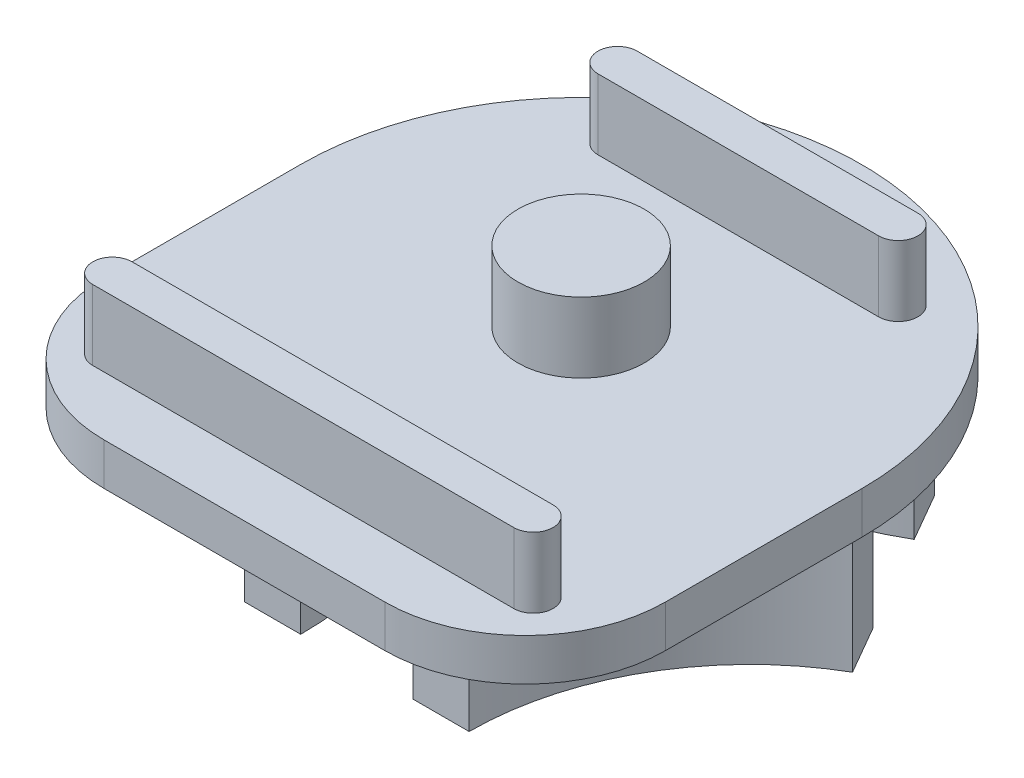
SolidWorks part; units mm, degrees
ref_plane "Front Plane" through (0, 0, 0) normal (0, 0, 1) x (1, 0, 0)
ref_plane "Top Plane" through (0, 0, 0) normal (0, 1, 0) x (1, 0, 0)
ref_plane "Right Plane" through (0, 0, 0) normal (1, 0, 0) x (0, 0, -1)
sketch "Sketch1" plane through (0, 0, 0) normal (0, 1, 0) x (1, 0, 0)
  circle A0 centre (0, 0) radius 28
  circle A1 centre (-28, -48.4974) radius 28
  circle A2 centre (28, -48.4974) radius 28
  arc A3 (-4.6726, -29.6339) -> (4.6726, -29.6339) centre (0, 0) ccw
  arc A4 (0, -37.7271) -> (-4.6726, -29.6339) centre (-28, -48.4974) ccw
  arc A5 (4.6726, -29.6339) -> (0, -37.7271) centre (28, -48.4974) ccw
  circle A6 centre (0, 0) radius 30 construction
  circle A7 centre (-28, -48.4974) radius 30 construction
  circle A8 centre (28, -48.4974) radius 30 construction
  circle A9 centre (0, 0) radius 24
  circle A10 centre (-28, -48.4974) radius 24
  circle A11 centre (28, -48.4974) radius 24
  circle A12 centre (0, 0) radius 20
  circle A13 centre (-28, -48.4974) radius 20
  circle A14 centre (28, -48.4974) radius 20
  dimension "D1" = 56
  dimension "D2" = 2
  dimension "D3" = 4
  dimension "D4" = 4
extrude "Boss-Extrude1" add sketch "Sketch1" along normal blind 10 contours A10 A13 | A9 A12 | A11 A14 | A5 A3 A4
sketch "Sketch2" plane through (0, 10, 0) normal (0, 1, 0) x (1, 0, 0)
  line L0 (-20, -32.517) -> (-20, -56.5059)
  line L1 (-20, -56.5059) -> (20, -56.5059)
  line L2 (20, -56.5059) -> (20, -32.517)
  arc A0 (20, -32.517) -> (-20, -32.517) centre (0, -32.517) ccw
  dimension "D1" = 40
extrude "Boss-Extrude2" add sketch "Sketch2" along normal blind 3
sketch "Sketch3" plane through (0, 0, 0) normal (0, -1, 0) x (1, 0, 0)
  line L0 (0, 0) -> (28, 48.4974)
  line L1 (28, 48.4974) -> (-28, 48.4974)
  line L2 (-28, 48.4974) -> (0, 0)
  line L4 (-59.3942, 74.2986) -> (61.8263, 74.2986)
  line L5 (-59.3942, 74.2986) -> (-59.3942, -27.4652)
  line L6 (-59.3942, -27.4652) -> (61.8263, -27.4652)
  line L7 (61.8263, 74.2986) -> (61.8263, -27.4652)
  circle A0 centre (-28, 48.4974) radius 20 construction
  circle A1 centre (28, 48.4974) radius 20 construction
extrude "Cut-Extrude1" cut sketch "Sketch3" against normal blind 10
sketch "Sketch4" plane through (0, 13, 0) normal (0, 1, 0) x (1, 0, 0)
  line L0 (-10, -19.917) -> (10, -19.917) construction
  line L1 (-10, -18.517) -> (10, -18.517)
  line L2 (-10, -21.317) -> (10, -21.317)
  line L3 (-15, -50.917) -> (15, -50.917) construction
  line L4 (-15, -49.517) -> (15, -49.517)
  line L5 (-15, -52.317) -> (15, -52.317)
  circle A0 centre (0, -32.517) radius 4.5
  arc A1 (-10, -18.517) -> (-10, -21.317) centre (-10, -19.917) ccw
  arc A2 (10, -21.317) -> (10, -18.517) centre (10, -19.917) ccw
  arc A3 (-15, -49.517) -> (-15, -52.317) centre (-15, -50.917) ccw
  arc A4 (15, -52.317) -> (15, -49.517) centre (15, -50.917) ccw
  circle A5 centre (0, -32.517) radius 20 construction
  point P4 (0, -19.917)
  point P9 (0, -50.917)
  dimension "D1" = 9
  dimension "D2" = 12.6
  dimension "D3" = 2.8
  dimension "D4" = 20
  dimension "D5" = 2.8
  dimension "D6" = 30
  dimension "D7" = 18.4
extrude "Boss-Extrude4" add sketch "Sketch4" along normal blind 5
fillet "Fillet1" radius 10 2 edges at (-20, 11.5, 56.5059) (20, 11.5, 56.5059)
